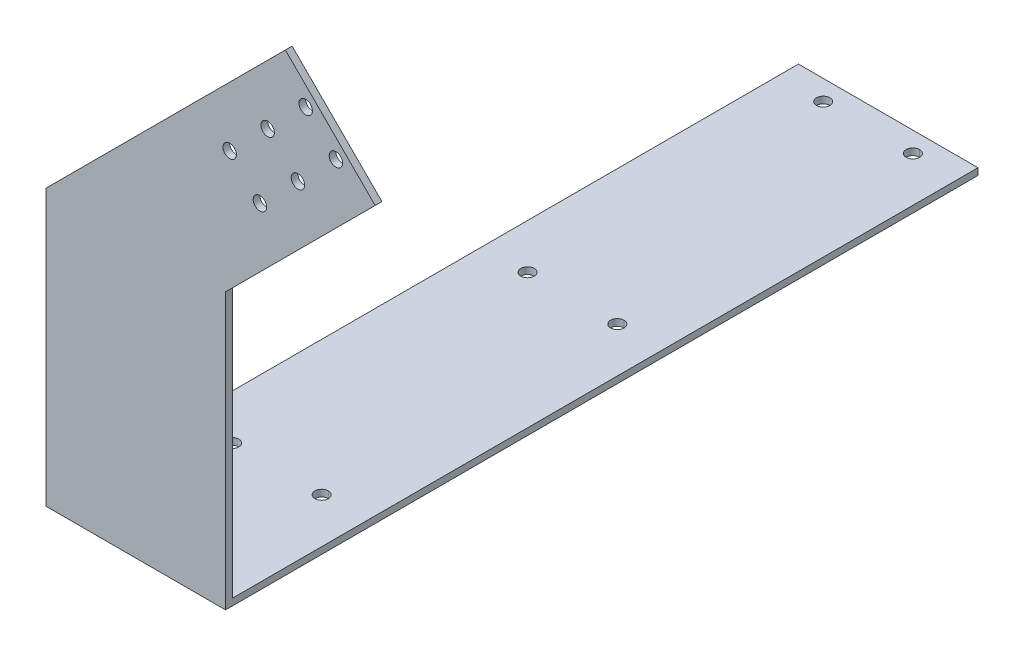
SolidWorks part; units mm, degrees
material "Malleable Cast Iron"
ref_plane "Front Plane" through (0, 0, 0) normal (0, 0, 1) x (1, 0, 0)
ref_plane "Top Plane" through (0, 0, 0) normal (0, 1, 0) x (1, 0, 0)
ref_plane "Right Plane" through (0, 0, 0) normal (1, 0, 0) x (0, 0, -1)
sketch "Sketch1" plane through (0, 0, 0) normal (0, 0, 1) x (1, 0, 0)
  line L0 (-2155.317, 3225.8) -> (3592.0469, 8973.1639)
  line L1 (2155.317, -3225.8) -> (-2155.317, -3225.8)
  line L2 (2155.317, -3225.8) -> (2155.317, 3225.8)
  line L4 (-2155.317, -3225.8) -> (-2155.317, 3225.8)
  line L5 (2155.317, -3225.8) -> (-2155.317, 3225.8) construction
  line L6 (2155.317, 3225.8) -> (-2155.317, -3225.8) construction
  line L7 (2155.317, 3225.8) -> (5747.4194, 6817.9024)
  line L8 (3592.0469, 8973.1639) -> (5747.4194, 6817.9024)
  line L9 (4669.7332, 7895.5332) -> (164.403, 3389.9708) construction
  circle A7 centre (4804.8334, 7304.2547) radius 161.29
  circle A8 centre (3892.4393, 6391.8607) radius 161.29
  circle A9 centre (2980.0453, 5479.4667) radius 161.29
  circle A10 centre (2253.7537, 6205.7208) radius 161.29
  circle A11 centre (3166.1007, 7118.1619) radius 161.29
  circle A12 centre (4078.4478, 8030.6029) radius 161.29
  point P0 (0, 0)
  dimension "D8" = 322.58
  dimension "D9" = 322.58
  dimension "D10" = 3
  dimension "D11" = 1290.32
  dimension "D1" = 4310.634
  dimension "D2" = 6451.6
  dimension "D3" = 135
  dimension "D4" = 135
  dimension "D5" = 8128
  dimension "D6" = 5080
  dimension "D7" = 3048.0785
  dimension "D15" = 1010.412
extrude "Boss-Extrude1" add sketch "Sketch1" against normal blind 161.29
ref_plane "Plane1" through (0, -3225.8, 0) normal (0, -1, 0) x (-1, 0, 0)
sketch "Sketch3" plane through (0, -3225.8, 0) normal (0, -1, 0) x (-1, 0, 0)
  line L0 (2155.317, 0) -> (-2155.317, 0) construction
  line L1 (-2155.317, 0) -> (2155.317, 0)
  line L2 (-2155.317, 0) -> (-2155.317, 18064.48)
  line L3 (-2155.317, 18064.48) -> (2155.317, 18064.48)
  line L4 (2155.317, 0) -> (2155.317, 18064.48)
  line L5 (2155.317, 161.29) -> (2155.317, 0) construction
  line L6 (2155.317, 161.29) -> (-2155.317, 161.29) construction
  line L8 (0, 18064.48) -> (0, 5163.8296) construction
  circle A0 centre (-1077.595, 17580.61) radius 161.29
  circle A2 centre (-1077.595, 10483.85) radius 161.29
  circle A3 centre (-1075.055, 17580.61) radius 161.29
  circle A4 centre (-1075.055, 10483.85) radius 161.29
  circle A5 centre (-1075.055, 3387.09) radius 161.29
  circle A6 centre (-1077.595, 10483.85) radius 161.29
  circle A7 centre (-1077.595, 3387.09) radius 161.29
  circle A8 centre (1075.055, 3387.09) radius 161.29
  circle A9 centre (1077.595, 10483.85) radius 161.29
  circle A10 centre (1077.595, 17580.61) radius 161.29
  point P0 (0, 0)
  point P14 (0, 0)
  point P34 (0, 0)
  point P35 (0, 0)
  point P36 (0, 0)
  point P37 (0, 0)
  point P38 (0, 0)
  dimension "D3" = 322.58
  dimension "D4" = 2
  dimension "D5" = 322.58
  dimension "D6" = 3
  dimension "D7" = 3225.8
  dimension "D8" = 7096.76
  dimension "D9" = 7096.76
  dimension "D1" = 4310.634
  dimension "D2" = 18064.48
  dimension "D10" = 2150.11
  dimension "D12" = 1077.722
extrude "Boss-Extrude3" add sketch "Sketch3" along normal blind 161.29
scale "Scale2" scale about centroid uniform scaling yes scale factor 0.03937
